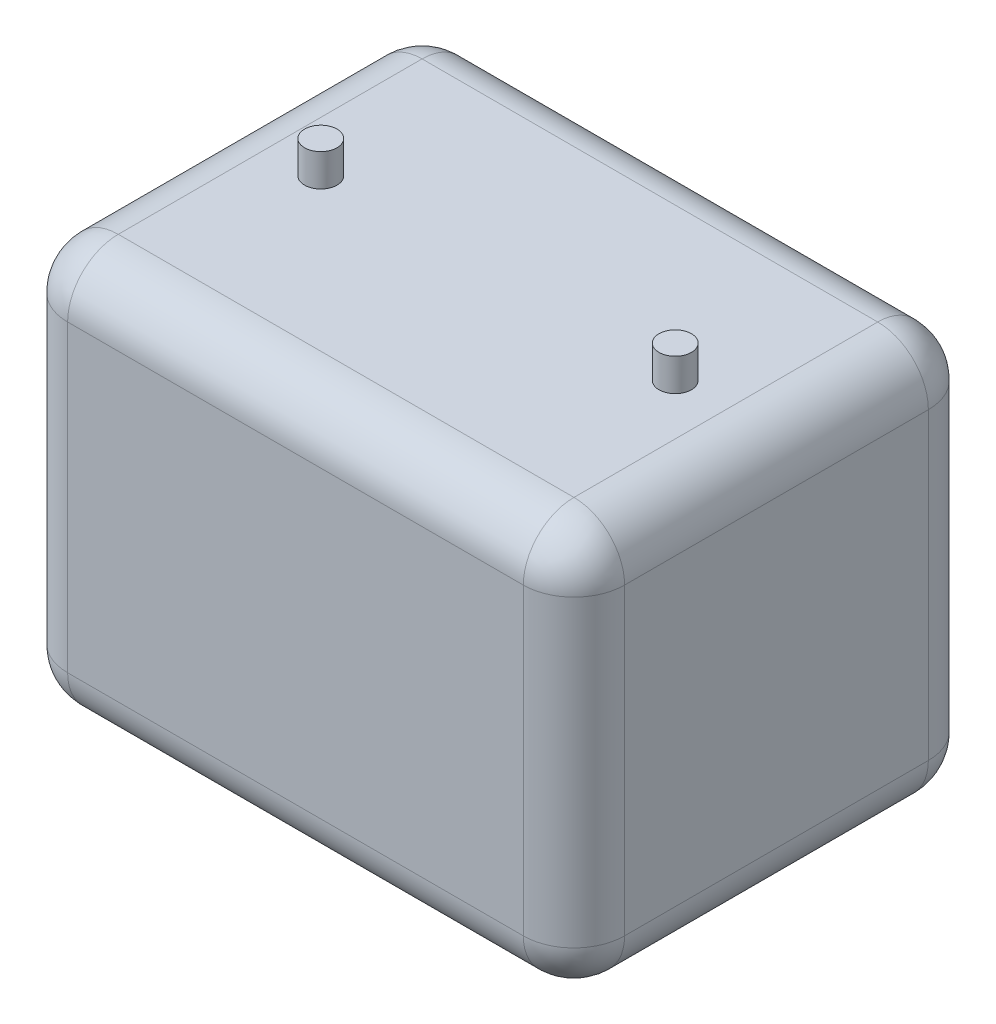
SolidWorks part; units mm, degrees
ref_plane "Front Plane" through (0, 0, 0) normal (0, 0, 1) x (1, 0, 0)
ref_plane "Top Plane" through (0, 0, 0) normal (0, 1, 0) x (1, 0, 0)
ref_plane "Right Plane" through (0, 0, 0) normal (1, 0, 0) x (0, 0, -1)
sketch "Sketch1" plane through (0, 0, 0) normal (0, 0, 1) x (1, 0, 0)
  line L1 (-27.5, 20) -> (27.5, 20)
  line L2 (-27.5, 20) -> (-27.5, -20)
  line L3 (-27.5, -20) -> (27.5, -20)
  line L4 (27.5, 20) -> (27.5, -20)
  line L5 (-27.5, 20) -> (27.5, -20) construction
  line L6 (-27.5, -20) -> (27.5, 20) construction
  point P0 (0, 0)
  dimension "D1" = 55
  dimension "D2" = 40
extrude "Boss-Extrude1" add sketch "Sketch1" along normal blind 40
sketch "Sketch2" plane through (0, 20, 0) normal (0, 1, 0) x (1, 0, 0)
  line L0 (-27.5, -20) -> (27.5, -20) construction
  line L1 (-27.5, -40) -> (-27.5, 0) construction
  line L2 (27.5, -40) -> (27.5, 0) construction
  line L3 (0, 0) -> (0, -40) construction
  line L4 (27.5, -40) -> (-27.5, -40) construction
  circle A0 centre (-17.5, -20) radius 1.6
  circle A1 centre (17.5, -20) radius 1.6
  dimension "D1" = 10
  dimension "D2" = 3.2
  dimension "D3" = 3.2
  dimension "D4" = 10
extrude "Boss-Extrude2" add sketch "Sketch2" along normal blind 3.2
sketch "Sketch3" plane through (0, -20, 0) normal (0, -1, 0) x (1, 0, 0)
  line L0 (0, 40) -> (0, 0) construction
  line L1 (-27.5, 40) -> (27.5, 40) construction
  line L2 (-27.5, 20) -> (27.5, 20) construction
  line L3 (-27.5, 40) -> (-27.5, 0) construction
  line L4 (27.5, 40) -> (27.5, 0) construction
  circle A0 centre (-17.5, 20) radius 1.6
  circle A1 centre (17.5, 20) radius 1.6
  dimension "D1" = 10
  dimension "D3" = 3.2
  dimension "D4" = 3.2
  dimension "D2" = 10
extrude "Boss-Extrude3" add sketch "Sketch3" along normal blind 3.2
fillet "Fillet2" radius 5 2 edges at (-27.5, -20, 20) (-27.5, 20, 20)
fillet "Fillet3" radius 5 2 edges at (27.5, -20, 20) (27.5, 20, 20)
fillet "Fillet4" radius 5 8 edges at (26.0355, 18.5355, 40) (27.5, 0, 40) (26.0355, -18.5355, 40) (0, -20, 40) (-26.0355, -18.5355, 40) (-27.5, 0, 40) (-26.0355, 18.5355, 40) (0, 20, 40)
fillet "Fillet5" radius 5 8 edges at (26.0355, 18.5355, 0) (27.5, 0, 0) (26.0355, -18.5355, 0) (0, -20, 0) (-26.0355, -18.5355, 0) (-27.5, 0, 0) (-26.0355, 18.5355, 0) (0, 20, 0)
